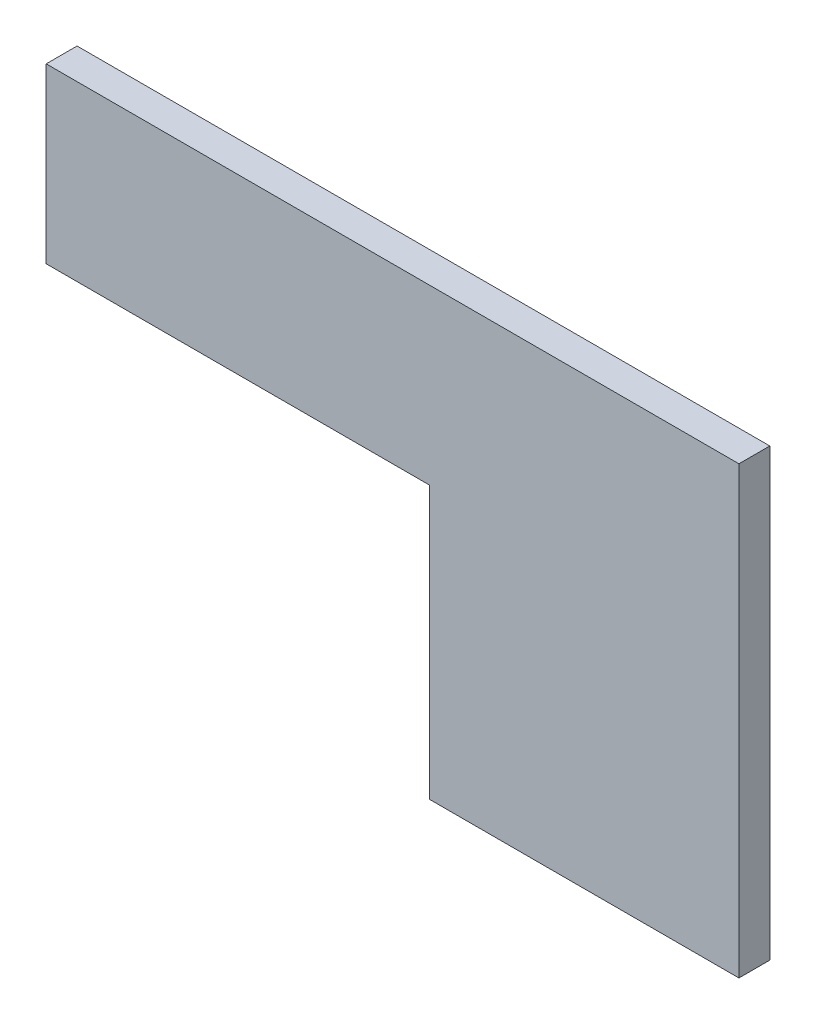
SolidWorks part; units mm, degrees
ref_plane "Front Plane" through (0, 0, 0) normal (0, 0, 1) x (1, 0, 0)
ref_plane "Top Plane" through (0, 0, 0) normal (0, 1, 0) x (1, 0, 0)
ref_plane "Right Plane" through (0, 0, 0) normal (1, 0, 0) x (0, 0, -1)
sketch "Sketch1" plane through (0, 0, 0) normal (0, 0, 1) x (1, 0, 0)
  line L1 (0, 0) -> (177.8, 0)
  line L2 (0, 0) -> (0, 114.3)
  line L3 (0, 114.3) -> (177.8, 114.3)
  line L4 (177.8, 0) -> (177.8, 114.3)
extrude "Boss-Extrude1" add sketch "Sketch1" along normal blind 7.9248
sketch "Sketch2" plane through (0, 0, 0) normal (0, 0, 1) x (1, 0, 0)
  line L1 (0, 0) -> (98.425, 0)
  line L2 (0, 0) -> (0, 69.85)
  line L3 (0, 69.85) -> (98.425, 69.85)
  line L4 (98.425, 0) -> (98.425, 69.85)
extrude "Cut-Extrude1" cut sketch "Sketch2" along normal through all
sketch "Sketch3" plane through (0, 0, 0) normal (0, 0, 1) x (1, 0, 0)
  circle A0 centre (0, 57.15) radius 2.9972
sketch "Sketch4" plane through (0, 0, 0) normal (0, 0, 1) x (1, 0, 0)
  circle A0 centre (0, 57.15) radius 5.3594
